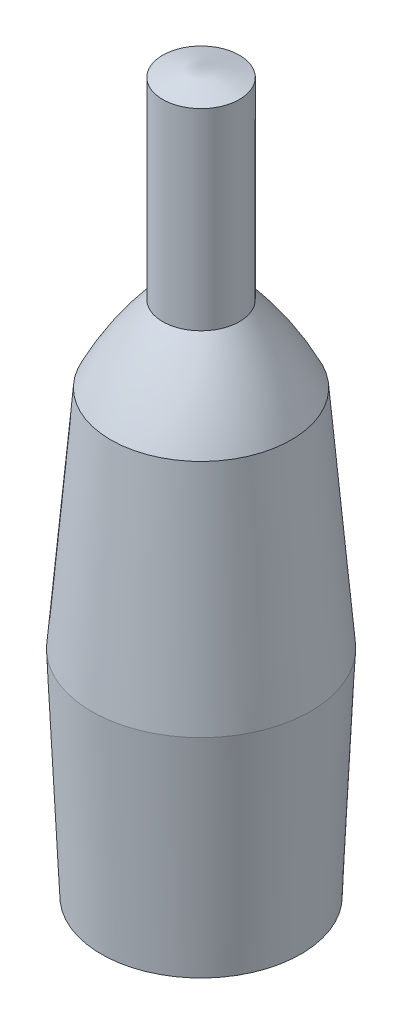
SolidWorks part; units mm, degrees
ref_plane "Front Plane" through (0, 0, 0) normal (0, 0, 1) x (1, 0, 0)
ref_plane "Top Plane" through (0, 0, 0) normal (0, 1, 0) x (1, 0, 0)
ref_plane "Right Plane" through (0, 0, 0) normal (1, 0, 0) x (0, 0, -1)
sketch "Sketch1" plane through (0, 0, 0) normal (1, 0, 0) x (0, 0, -1)
  line L0 (-38.7676, 121.4674) -> (47.3973, 121.4674) construction
  line L1 (0, 0) -> (0, 285) construction
  line L2 (0, 285) -> (-15.1838, 280.7135)
  line L3 (-15.1838, 280.7135) -> (-15.1838, 204.5739)
  line L4 (-35.7241, 174.3286) -> (-43.2731, 85.0437)
  line L5 (-43.2731, 85.0437) -> (-39.4986, 0)
  line L6 (-39.4986, 0) -> (0, 0)
  line L7 (0, 0) -> (0, 285)
  arc A0 (-15.1838, 204.5739) -> (-35.7241, 174.3286) centre (80.7757, 117.3082) ccw
revolve "Revolve1" add sketch "Sketch1" angle 360 about L7
